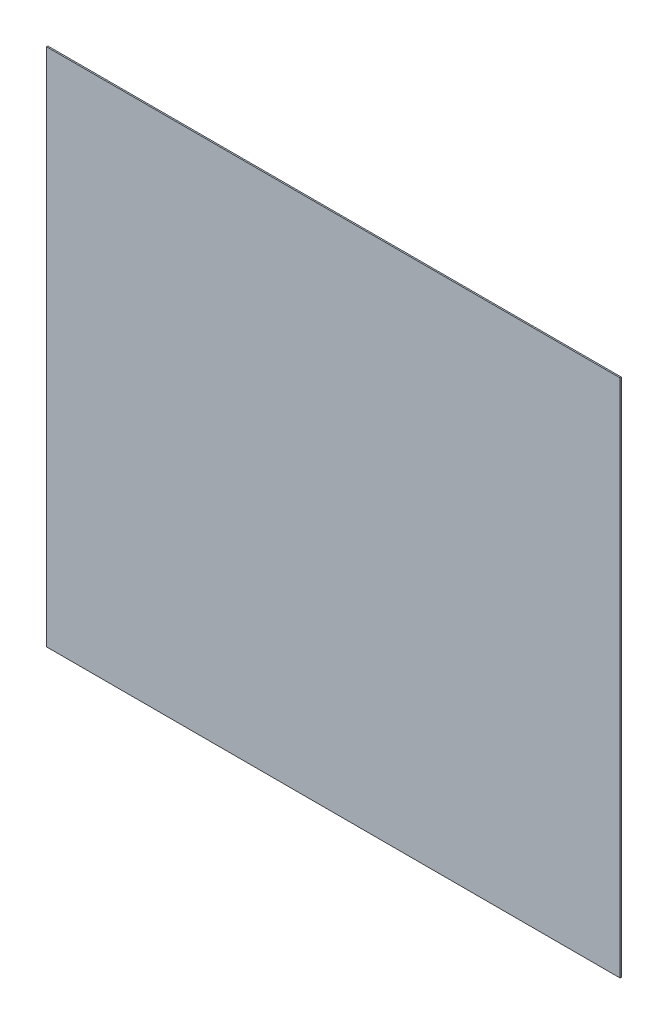
SolidWorks part; units mm, degrees
ref_plane "Front Plane" through (0, 0, 0) normal (0, 0, 1) x (1, 0, 0)
ref_plane "Top Plane" through (0, 0, 0) normal (0, 1, 0) x (1, 0, 0)
ref_plane "Right Plane" through (0, 0, 0) normal (1, 0, 0) x (0, 0, -1)
other "Configuration Table"
sketch "Sketch1" plane through (0, 0, 0) normal (0, 0, 1) x (1, 0, 0)
  line L1 (30, 120) -> (670, 120)
  line L2 (30, 120) -> (30, 700)
  line L3 (30, 700) -> (670, 700)
  line L4 (670, 120) -> (670, 700)
extrude "PRESS_panel_alt_1" add sketch "Sketch1" along normal blind 1.5 from offset 38.5 separate body
